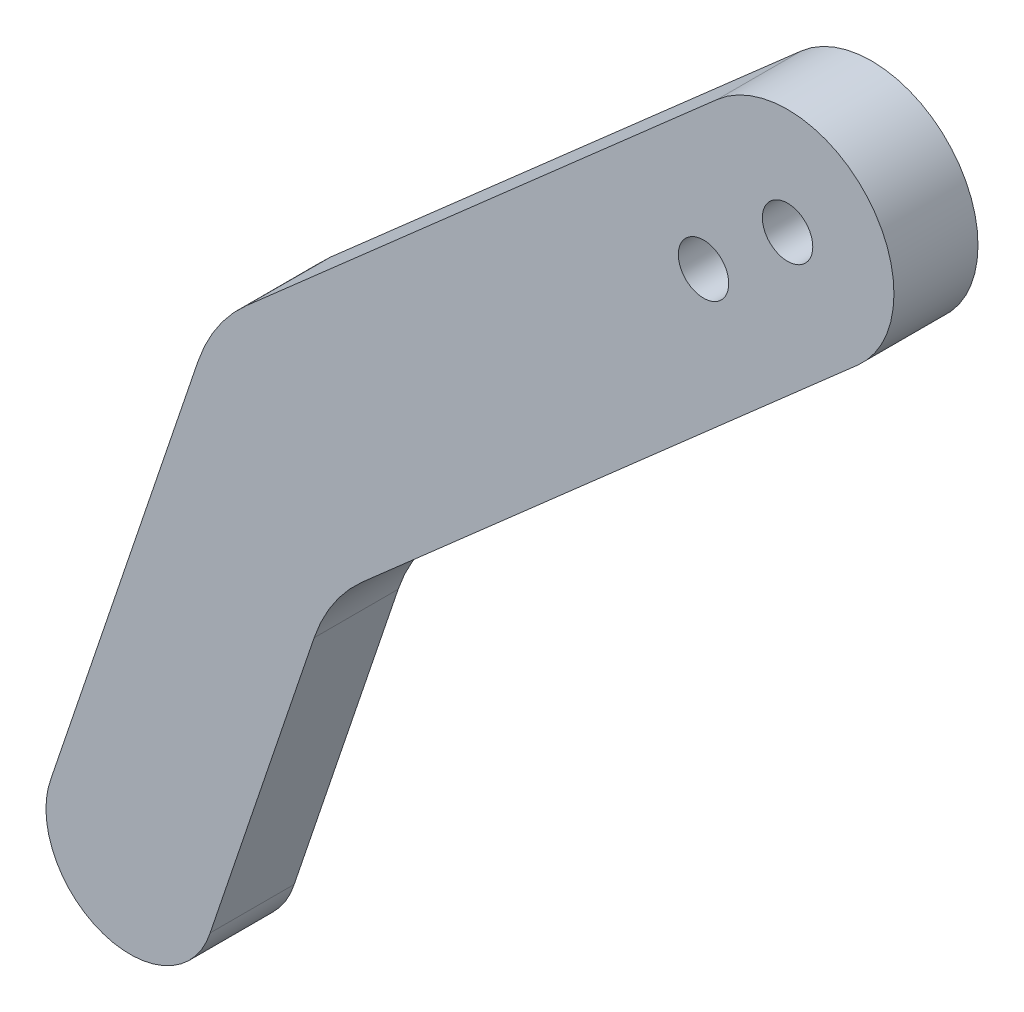
SolidWorks part; units mm, degrees
ref_plane "Front Plane" through (0, 0, 0) normal (0, 0, 1) x (1, 0, 0)
ref_plane "Top Plane" through (0, 0, 0) normal (0, 1, 0) x (1, 0, 0)
ref_plane "Right Plane" through (0, 0, 0) normal (1, 0, 0) x (0, 0, -1)
sketch "Sketch3" plane through (0, 0, 0) normal (0, 0, 1) x (1, 0, 0)
  line L0 (0, 0) -> (8.7494, 25.8816)
  line L1 (0, 0) -> (9.4733, -3.2025) construction
  line L2 (9.4733, -3.2025) -> (15.6607, 15.1004)
  line L3 (11.6198, 30.1892) -> (39.648, 54.8316)
  line L4 (39.648, 54.8316) -> (48.0074, 45.3236) construction
  line L5 (18.5312, 19.4081) -> (48.0074, 45.3236)
  arc A0 (39.648, 54.8316) -> (48.0074, 45.3236) centre (43.8277, 50.0776) cw
  arc A1 (0, 0) -> (9.4733, -3.2025) centre (4.7079, -1.6863) ccw
  arc A2 (8.7494, 25.8816) -> (11.6198, 30.1892) centre (18.2227, 22.6791) cw
  arc A3 (15.6607, 15.1004) -> (18.5312, 19.4081) centre (25.1341, 11.8979) cw
  point P10 (9.6075, 28.42)
  point P13 (19.9017, -5.697)
  point P15 (16.5188, 17.6388)
  dimension "D7" = 5.0008
  dimension "D8" = 10
  dimension "D9" = 10
  dimension "D1" = 30
  dimension "D2" = 40
  dimension "D3" = 150
  dimension "D4" = 31.4886
  dimension "D5" = 22
  dimension "D6" = 10
extrude "Boss-Extrude1" add sketch "Sketch3" along normal blind 5 contours L0 A1 L2 L5 A0 L3
sketch "Sketch4" plane through (0, 0, 5) normal (0, 0, 1) x (1, 0, 0)
  line L0 (39.648, 54.8316) -> (48.0074, 45.3236) construction
  line L1 (43.8277, 50.0776) -> (25.8103, 34.2367) construction
  circle A0 centre (43.8277, 50.0776) radius 1.5
  arc A1 (48.0074, 45.3236) -> (39.648, 54.8316) centre (43.8277, 50.0776) ccw construction
  circle A2 centre (38.8277, 45.6816) radius 1.5
  point P9 (43.8277, 50.0776)
  dimension "D1" = 3
  dimension "D2" = 5
  dimension "D3" = 3
extrude "Cut-Extrude1" cut sketch "Sketch4" against normal blind 7
